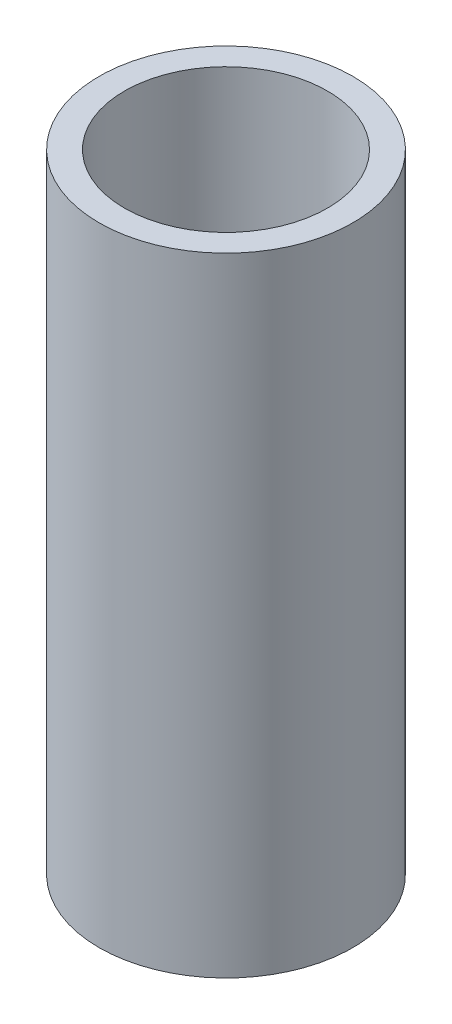
SolidWorks part; units mm, degrees
ref_plane "Front Plane" through (0, 0, 0) normal (0, 0, 1) x (1, 0, 0)
ref_plane "Top Plane" through (0, 0, 0) normal (0, 1, 0) x (1, 0, 0)
ref_plane "Right Plane" through (0, 0, 0) normal (1, 0, 0) x (0, 0, -1)
ref_plane "Plane1" through (0, 0, 0) normal (0, 0, 1) x (1, 0, 0)
sketch "Sketch1" plane through (0, 0, 0) normal (0, 0, 1) x (1, 0, 0)
  line L0 (1.52, 9.4) -> (1.52, 0)
  line L1 (1.52, 0) -> (1.9, 0)
  line L2 (1.9, 0) -> (1.9, 9.4)
  line L3 (1.9, 9.4) -> (1.52, 9.4)
  line L4 (0, 0) -> (0, 9.4) construction
revolve "Revolve1" add sketch "Sketch1" angle 360 about L4
